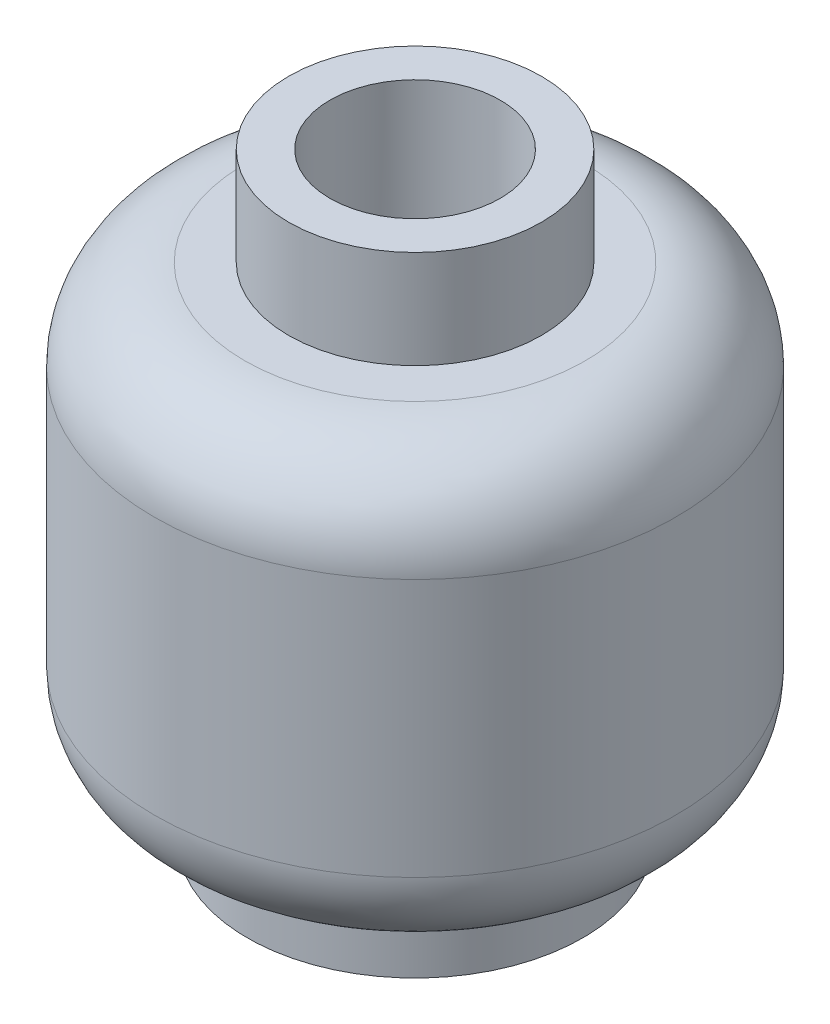
SolidWorks part; units mm, degrees
ref_plane "Front Plane" through (0, 0, 0) normal (0, 0, 1) x (1, 0, 0)
ref_plane "Top Plane" through (0, 0, 0) normal (0, 1, 0) x (1, 0, 0)
ref_plane "Right Plane" through (0, 0, 0) normal (1, 0, 0) x (0, 0, -1)
sketch "Sketch1" plane through (0, 0, 0) normal (0, 1, 0) x (1, 0, 0)
  circle A0 centre (0, 0) radius 3.25
  dimension "D1" = 6.5
extrude "Boss-Extrude1" add sketch "Sketch1" along normal blind 1.21
sketch "Sketch2" plane through (0, 1.21, 0) normal (0, 1, 0) x (1, 0, 0)
  circle A0 centre (0, 0) radius 5.05
  dimension "D1" = 10.1
extrude "Boss-Extrude2" add sketch "Sketch2" along normal blind 8.5
sketch "Sketch3" plane through (0, 9.71, 0) normal (0, 1, 0) x (1, 0, 0)
  circle A0 centre (0, 0) radius 2.45
  dimension "D1" = 4.9
extrude "Boss-Extrude3" add sketch "Sketch3" along normal blind 1.9
fillet "Fillet1" radius 1.75 1 edges at (0, 9.71, 5.05)
fillet "Fillet2" radius 1.75 1 edges at (0, 1.21, 5.05)
sketch "Sketch4" plane through (0, 11.61, 0) normal (0, 1, 0) x (1, 0, 0)
  circle A0 centre (0, 0) radius 1.65
  circle A1 centre (0, 0) radius 2.45 construction
  dimension "D1" = 0.8
extrude "Cut-Extrude1" cut sketch "Sketch4" against normal through all
sketch "Sketch5" plane through (0, 0, 0) normal (0, -1, 0) x (1, 0, 0)
  circle A0 centre (0, 0) radius 2.45
  circle A1 centre (0, 0) radius 3.25 construction
  dimension "D1" = 0.8
extrude "Cut-Extrude3" cut sketch "Sketch5" against normal blind 8.6
